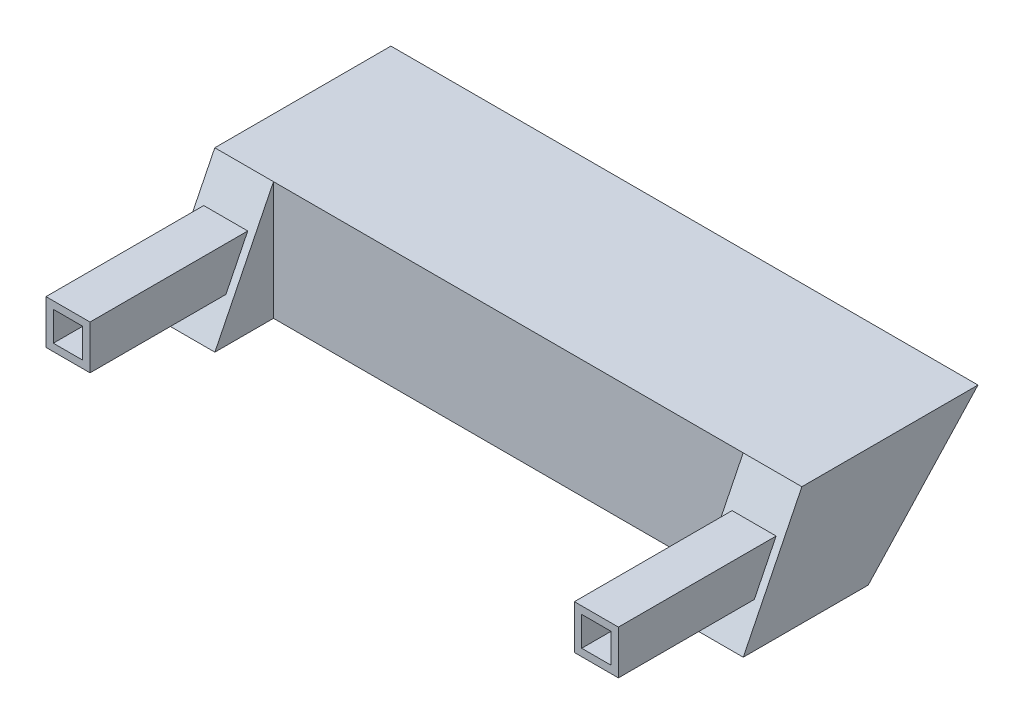
SolidWorks part; units mm, degrees
ref_plane "Front Plane" through (0, 0, 0) normal (0, 0, 1) x (1, 0, 0)
ref_plane "Top Plane" through (0, 0, 0) normal (0, 1, 0) x (1, 0, 0)
ref_plane "Right Plane" through (0, 0, 0) normal (1, 0, 0) x (0, 0, -1)
sketch "Sketch1" plane through (0, 0, 0) normal (1, 0, 0) x (0, 0, -1)
  line L0 (0, 0) -> (0, 51.2149)
  line L1 (0, 51.2149) -> (76.2, 51.2149)
  line L2 (76.2, 51.2149) -> (28.702, 0)
  line L3 (28.702, 0) -> (0, 0)
  point P3 (-22.0426, 66.699)
  point P5 (0, 0)
  dimension "D1" = 28.702
  dimension "D2" = 69.85
  dimension "D3" = 76.2
extrude "Boss-Extrude1" add sketch "Sketch1" along normal mid plane 254
sketch "Sketch3" plane through (0, 0, 0) normal (1, 0, 0) x (0, 0, -1)
  line L0 (0, 51.2149) -> (-25.3606, 0)
  line L1 (0, 55) -> (0, -55) construction
  line L2 (76.2, 51.2149) -> (0, 51.2149) construction
  line L3 (55, 0) -> (-55, 0) construction
  line L4 (-25.3606, 0) -> (0, 0)
  line L5 (0, 51.2149) -> (0, 0)
  dimension "D1" = 57.15
extrude "Boss-Extrude2" add sketch "Sketch3" along normal blind 25.4 from offset 101.6
mirror "Mirror1" about plane through (0, 0, 0) normal (1, 0, 0) of "Boss-Extrude2"
sketch "Sketch4" plane through (0, 0, 0) normal (0, 0, 1) x (1, 0, 0)
  line L0 (101.6, 51.2149) -> (127, 51.2149) construction
  line L1 (104.775, 35.1324) -> (123.825, 35.1324)
  line L2 (104.775, 35.1324) -> (104.775, 16.0824)
  line L3 (104.775, 16.0824) -> (123.825, 16.0824)
  line L4 (123.825, 35.1324) -> (123.825, 16.0824)
  line L5 (107.95, 31.9574) -> (120.65, 31.9574)
  line L6 (107.95, 31.9574) -> (107.95, 19.2574)
  line L7 (107.95, 19.2574) -> (120.65, 19.2574)
  line L8 (120.65, 31.9574) -> (120.65, 19.2574)
  line L9 (101.6, 51.2149) -> (101.6, 0) construction
  point P8 (114.3, 19.2574)
  point P9 (114.3, 16.0824)
  point P10 (120.65, 25.6074)
  point P11 (123.825, 25.6074)
  point P12 (114.3, 51.2149)
  point P17 (114.3, 35.1324)
  point P18 (101.6, 25.6074)
  point P21 (107.95, 25.6074)
  dimension "D1" = 19.05
  dimension "D2" = 12.7
extrude "Boss-Extrude3" add sketch "Sketch4" along normal blind 76.2
mirror "Mirror2" about plane through (0, 0, 0) normal (1, 0, 0) of "Boss-Extrude3"
equation "\"height\"= 2in"
equation "\"top length\"= 3in"
equation "\"bottom length\" = 1.13in"
equation "\"diag face\"= 2.75in"
equation "\"interface diag\"= 2.25in"
equation "\"D1@Sketch1\"=\"bottom length\""
equation "\"D2@Sketch1\"=\"diag face\""
equation "\"D3@Sketch1\"=\"top length\""
equation "\"width\"= 10in"
equation "\"D1@Boss-Extrude1\"=\"width\""
equation "\"D1@Sketch3\"=\"interface diag\""
equation "\"interfacewidth\"= 1in"
equation "\"D19@Boss-Extrude2\"=\"width\"/2  - \"interfacewidth\""
equation "\"D1@Boss-Extrude2\"=\"interfacewidth\""
equation "\"Connector OD\"= .75in"
equation "\"Connector ID\"= .5in"
equation "\"D1@Sketch4\"=\"Connector OD\""
equation "\"D2@Sketch4\"=\"Connector ID\""
equation "\"Connector Length\"= 3in"
equation "\"D1@Boss-Extrude3\"=\"Connector Length\""
